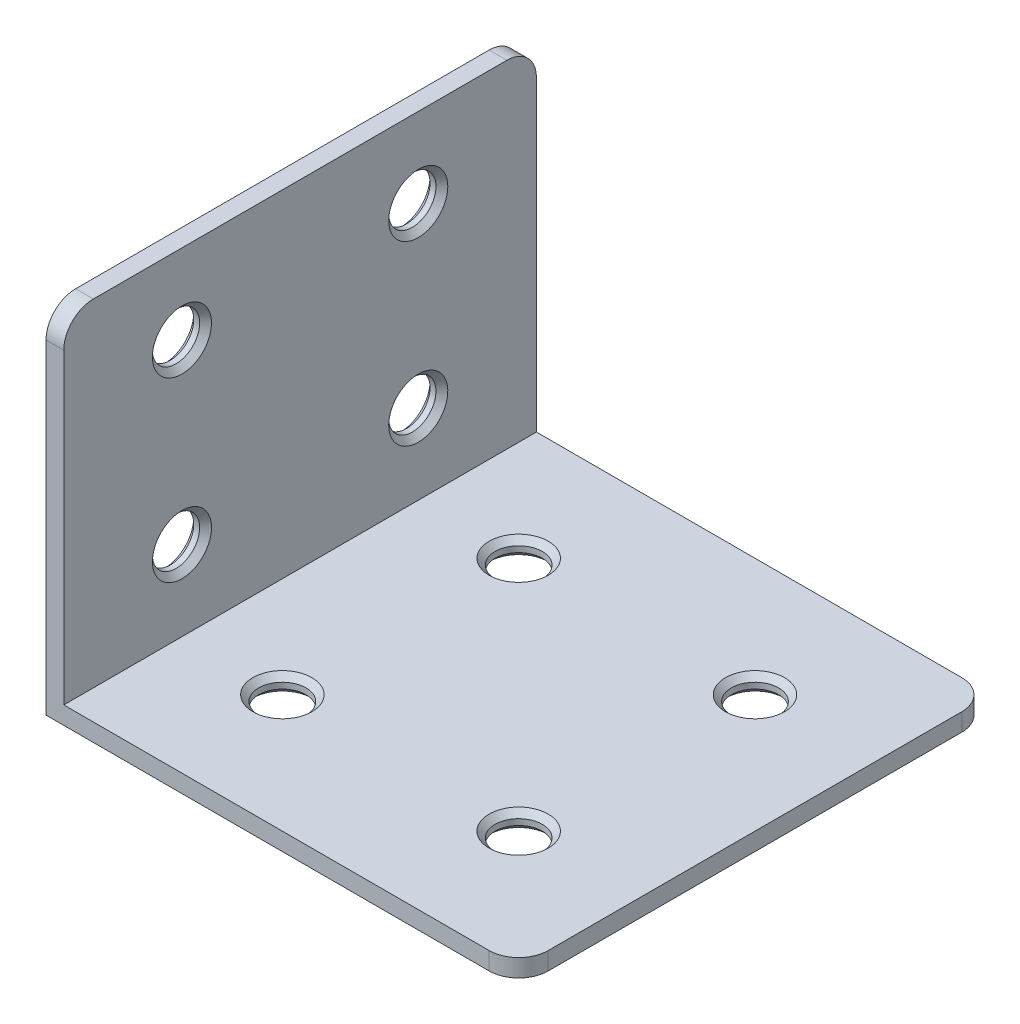
SolidWorks part; units mm, degrees
ref_plane "Płaszczyzna przednia" through (0, 0, 0) normal (0, 0, 1) x (1, 0, 0)
ref_plane "Płaszczyzna górna" through (0, 0, 0) normal (0, 1, 0) x (1, 0, 0)
ref_plane "Płaszczyzna prawa" through (0, 0, 0) normal (1, 0, 0) x (0, 0, -1)
sketch "Szkic1" plane through (0, 0, 0) normal (0, 1, 0) x (1, 0, 0)
  line L1 (-40, -40) -> (40, -40)
  line L2 (-40, -40) -> (-40, 40)
  line L3 (-40, 40) -> (40, 40)
  line L4 (40, -40) -> (40, 40)
  line L5 (-40, -40) -> (40, 40) construction
  line L6 (-40, 40) -> (40, -40) construction
  point P0 (0, 0)
  dimension "D1" = 80
  dimension "D2" = 80
extrude "Dodanie-wyciągnięcie1" add sketch "Szkic1" along normal blind 60
sketch "Szkic2" plane through (0, 0, 40) normal (0, 0, 1) x (1, 0, 0)
  line L0 (-40, 60) -> (-40, 0) construction
  line L1 (40, 60) -> (-37, 60)
  line L2 (40, 60) -> (40, 3)
  line L3 (40, 3) -> (-37, 3)
  line L4 (-37, 60) -> (-37, 3)
  line L5 (-40, 0) -> (40, 0) construction
  dimension "D1" = 3
  dimension "D2" = 3
extrude "Wytnij-wyciągnięcie1" cut sketch "Szkic2" against normal through all
sketch "Szkic3" plane through (-37, 0, 0) normal (1, 0, 0) x (0, 0, -1)
  line L0 (0, 64.2942) -> (0, -18.974) construction
  line L1 (-40, 31.5) -> (60.8295, 31.5) construction
  line L2 (-40, 60) -> (-40, 3) construction
  circle A0 centre (-20, 46.5) radius 4
  circle A1 centre (-20, 16.5) radius 4
  circle A2 centre (20, 16.5) radius 4
  circle A3 centre (20, 46.5) radius 4
  dimension "D1" = 8
  dimension "D2" = 30
  dimension "D3" = 40
sketch "Szkic4" plane through (0, 3, 0) normal (0, 1, 0) x (1, 0, 0)
  line L0 (-61.3075, 0) -> (82.259, 0) construction
  line L1 (0, 52.5285) -> (0, -50.4147) construction
  circle A0 centre (-20, 20) radius 4
  circle A1 centre (20, 20) radius 4
  circle A2 centre (20, -20) radius 4
  circle A3 centre (-20, -20) radius 4
  dimension "D3" = 8
  dimension "D1" = 40
  dimension "D2" = 40
extrude "Wytnij-wyciągnięcie2" cut sketch "Szkic4" against normal through all contours A2 | A1 | A0 | A3
extrude "Wytnij-wyciągnięcie3" cut sketch "Szkic3" against normal blind 60
fillet "Zaokrąglenie1" radius 5 4 edges at (40, 1.5, 40) (40, 1.5, -40) (-38.5, 60, -40) (-38.5, 60, 40)
chamfer "Sfazowanie1" distance 1 angle 45 16 edges at (-40, 16.5, 16) (-37, 12.5, 20) (-40, 46.5, 16) (-37, 50.5, 20) (-40, 46.5, -24) (-37, 42.5, -20) (-24, 3, -20) (-24, 0, -20) (16, 0, 20) (16, 0, -20) (-16, 0, 20) (-37, 20.5, -20) (-40, 16.5, -24) (16, 3, -20) (16, 3, 20) (-16, 3, 20)
